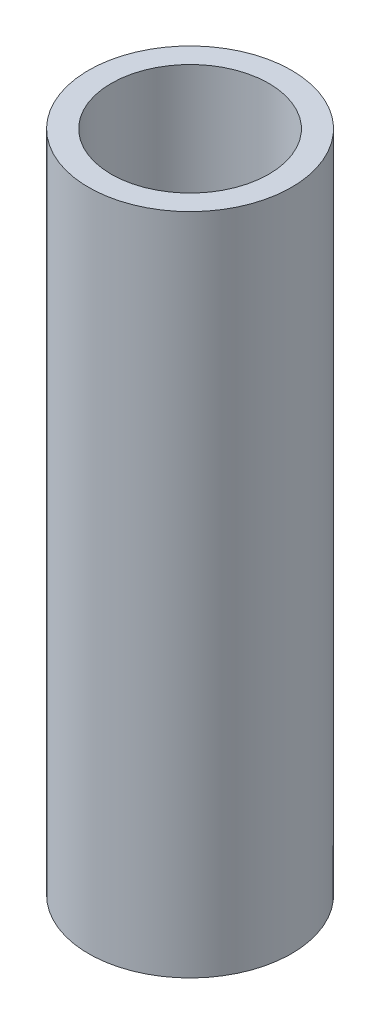
SolidWorks part; units mm, degrees
material "6061-T6 (SS)"
ref_plane "Front Plane" through (0, 0, 0) normal (0, 0, 1) x (1, 0, 0)
ref_plane "Top Plane" through (0, 0, 0) normal (0, 1, 0) x (1, 0, 0)
ref_plane "Right Plane" through (0, 0, 0) normal (1, 0, 0) x (0, 0, -1)
sketch "Sketch1" plane through (0, 0, 0) normal (0, 1, 0) x (1, 0, 0)
  circle A0 centre (0, 0) radius 3.0861
  circle A1 centre (0, 0) radius 3.9751
  dimension "D1" = 6.1722
  dimension "D2" = 0.889
extrude "Boss-Extrude1" add sketch "Sketch1" along normal mid plane 26
equation "\"length\"= 26"
equation "\"D1@Boss-Extrude1\"=\"length\""
